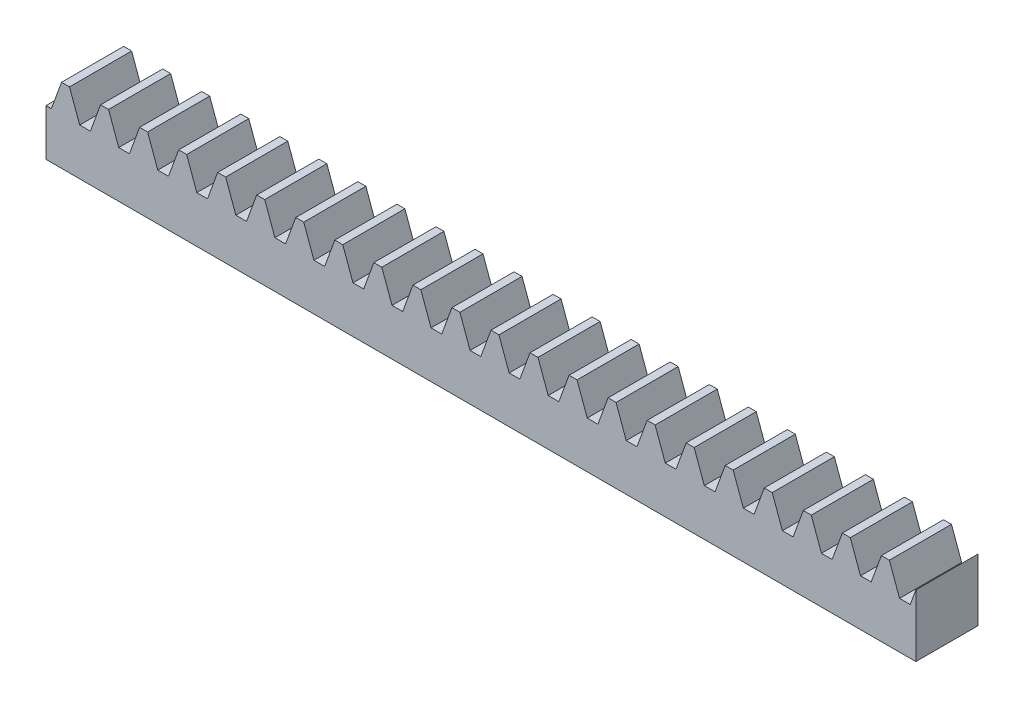
SolidWorks part; units mm, degrees
ref_plane "Front Plane" through (0, 0, 0) normal (0, 0, 1) x (1, 0, 0)
ref_plane "Top Plane" through (0, 0, 0) normal (0, 1, 0) x (1, 0, 0)
ref_plane "Right Plane" through (0, 0, 0) normal (1, 0, 0) x (0, 0, -1)
ref_plane "Plane1" through (0, 0, -10.1498) normal (0, 0, -1) x (-1, 0, 0)
sketch "Sketch1" plane through (0, 0, -10.1498) normal (0, 0, -1) x (-1, 0, 0)
  line L0 (-74.4643, 2.1443) -> (-76.1022, -2.3557)
  line L1 (-76.1022, -2.3557) -> (-77.8259, -2.3557)
  line L2 (-77.8259, -2.3557) -> (-78.734, 0.1391)
  line L3 (-78.734, 0.1391) -> (-78.734, -9.8557)
  line L4 (-78.734, -9.8557) -> (61.266, -9.8557)
  line L5 (61.266, -9.8557) -> (61.266, -2.3557)
  line L6 (61.266, -2.3557) -> (60.4042, -2.3557)
  line L7 (60.4042, -2.3557) -> (58.7663, 2.1443)
  line L8 (58.7663, 2.1443) -> (57.4826, 2.1443)
  line L9 (57.4826, 2.1443) -> (55.8447, -2.3557)
  line L10 (55.8447, -2.3557) -> (54.121, -2.3557)
  line L11 (54.121, -2.3557) -> (52.4831, 2.1443)
  line L12 (52.4831, 2.1443) -> (51.1994, 2.1443)
  line L13 (51.1994, 2.1443) -> (49.5615, -2.3557)
  line L14 (49.5615, -2.3557) -> (47.8378, -2.3557)
  line L15 (47.8378, -2.3557) -> (46.1999, 2.1443)
  line L16 (46.1999, 2.1443) -> (44.9162, 2.1443)
  line L17 (44.9162, 2.1443) -> (43.2784, -2.3557)
  line L18 (43.2784, -2.3557) -> (41.5546, -2.3557)
  line L19 (41.5546, -2.3557) -> (39.9168, 2.1443)
  line L20 (39.9168, 2.1443) -> (38.633, 2.1443)
  line L21 (38.633, 2.1443) -> (36.9952, -2.3557)
  line L22 (36.9952, -2.3557) -> (35.2714, -2.3557)
  line L23 (35.2714, -2.3557) -> (33.6336, 2.1443)
  line L24 (33.6336, 2.1443) -> (32.3499, 2.1443)
  line L25 (32.3499, 2.1443) -> (30.712, -2.3557)
  line L26 (30.712, -2.3557) -> (28.9882, -2.3557)
  line L27 (28.9882, -2.3557) -> (27.3504, 2.1443)
  line L28 (27.3504, 2.1443) -> (26.0667, 2.1443)
  line L29 (26.0667, 2.1443) -> (24.4288, -2.3557)
  line L30 (24.4288, -2.3557) -> (22.7051, -2.3557)
  line L31 (22.7051, -2.3557) -> (21.0672, 2.1443)
  line L32 (21.0672, 2.1443) -> (19.7835, 2.1443)
  line L33 (19.7835, 2.1443) -> (18.1456, -2.3557)
  line L34 (18.1456, -2.3557) -> (16.4219, -2.3557)
  line L35 (16.4219, -2.3557) -> (14.784, 2.1443)
  line L36 (14.784, 2.1443) -> (13.5003, 2.1443)
  line L37 (13.5003, 2.1443) -> (11.8624, -2.3557)
  line L38 (11.8624, -2.3557) -> (10.1387, -2.3557)
  line L39 (10.1387, -2.3557) -> (8.5008, 2.1443)
  line L40 (8.5008, 2.1443) -> (7.2171, 2.1443)
  line L41 (7.2171, 2.1443) -> (5.5792, -2.3557)
  line L42 (5.5792, -2.3557) -> (3.8555, -2.3557)
  line L43 (3.8555, -2.3557) -> (2.2176, 2.1443)
  line L44 (2.2176, 2.1443) -> (0.9339, 2.1443)
  line L45 (0.9339, 2.1443) -> (-0.7039, -2.3557)
  line L46 (-0.7039, -2.3557) -> (-2.4277, -2.3557)
  line L47 (-2.4277, -2.3557) -> (-4.0655, 2.1443)
  line L48 (-4.0655, 2.1443) -> (-5.3493, 2.1443)
  line L49 (-5.3493, 2.1443) -> (-6.9871, -2.3557)
  line L50 (-6.9871, -2.3557) -> (-8.7109, -2.3557)
  line L51 (-8.7109, -2.3557) -> (-10.3487, 2.1443)
  line L52 (-10.3487, 2.1443) -> (-11.6324, 2.1443)
  line L53 (-11.6324, 2.1443) -> (-13.2703, -2.3557)
  line L54 (-13.2703, -2.3557) -> (-14.994, -2.3557)
  line L55 (-14.994, -2.3557) -> (-16.6319, 2.1443)
  line L56 (-16.6319, 2.1443) -> (-17.9156, 2.1443)
  line L57 (-17.9156, 2.1443) -> (-19.5535, -2.3557)
  line L58 (-19.5535, -2.3557) -> (-21.2772, -2.3557)
  line L59 (-21.2772, -2.3557) -> (-22.9151, 2.1443)
  line L60 (-22.9151, 2.1443) -> (-24.1988, 2.1443)
  line L61 (-24.1988, 2.1443) -> (-25.8367, -2.3557)
  line L62 (-25.8367, -2.3557) -> (-27.5604, -2.3557)
  line L63 (-27.5604, -2.3557) -> (-29.1983, 2.1443)
  line L64 (-29.1983, 2.1443) -> (-30.482, 2.1443)
  line L65 (-30.482, 2.1443) -> (-32.1199, -2.3557)
  line L66 (-32.1199, -2.3557) -> (-33.8436, -2.3557)
  line L67 (-33.8436, -2.3557) -> (-35.4815, 2.1443)
  line L68 (-35.4815, 2.1443) -> (-36.7652, 2.1443)
  line L69 (-36.7652, 2.1443) -> (-38.403, -2.3557)
  line L70 (-38.403, -2.3557) -> (-40.1268, -2.3557)
  line L71 (-40.1268, -2.3557) -> (-41.7647, 2.1443)
  line L72 (-41.7647, 2.1443) -> (-43.0484, 2.1443)
  line L73 (-43.0484, 2.1443) -> (-44.6862, -2.3557)
  line L74 (-44.6862, -2.3557) -> (-46.41, -2.3557)
  line L75 (-46.41, -2.3557) -> (-48.0478, 2.1443)
  line L76 (-48.0478, 2.1443) -> (-49.3316, 2.1443)
  line L77 (-49.3316, 2.1443) -> (-50.9694, -2.3557)
  line L78 (-50.9694, -2.3557) -> (-52.6932, -2.3557)
  line L79 (-52.6932, -2.3557) -> (-54.331, 2.1443)
  line L80 (-54.331, 2.1443) -> (-55.6147, 2.1443)
  line L81 (-55.6147, 2.1443) -> (-57.2526, -2.3557)
  line L82 (-57.2526, -2.3557) -> (-58.9763, -2.3557)
  line L83 (-58.9763, -2.3557) -> (-60.6142, 2.1443)
  line L84 (-60.6142, 2.1443) -> (-61.8979, 2.1443)
  line L85 (-61.8979, 2.1443) -> (-63.5358, -2.3557)
  line L86 (-63.5358, -2.3557) -> (-65.2595, -2.3557)
  line L87 (-65.2595, -2.3557) -> (-66.8974, 2.1443)
  line L88 (-66.8974, 2.1443) -> (-68.1811, 2.1443)
  line L89 (-68.1811, 2.1443) -> (-69.819, -2.3557)
  line L90 (-69.819, -2.3557) -> (-71.5427, -2.3557)
  line L91 (-71.5427, -2.3557) -> (-73.1806, 2.1443)
  line L92 (-73.1806, 2.1443) -> (-74.4643, 2.1443)
extrude "Boss-Extrude1" add sketch "Sketch1" against normal blind 10
